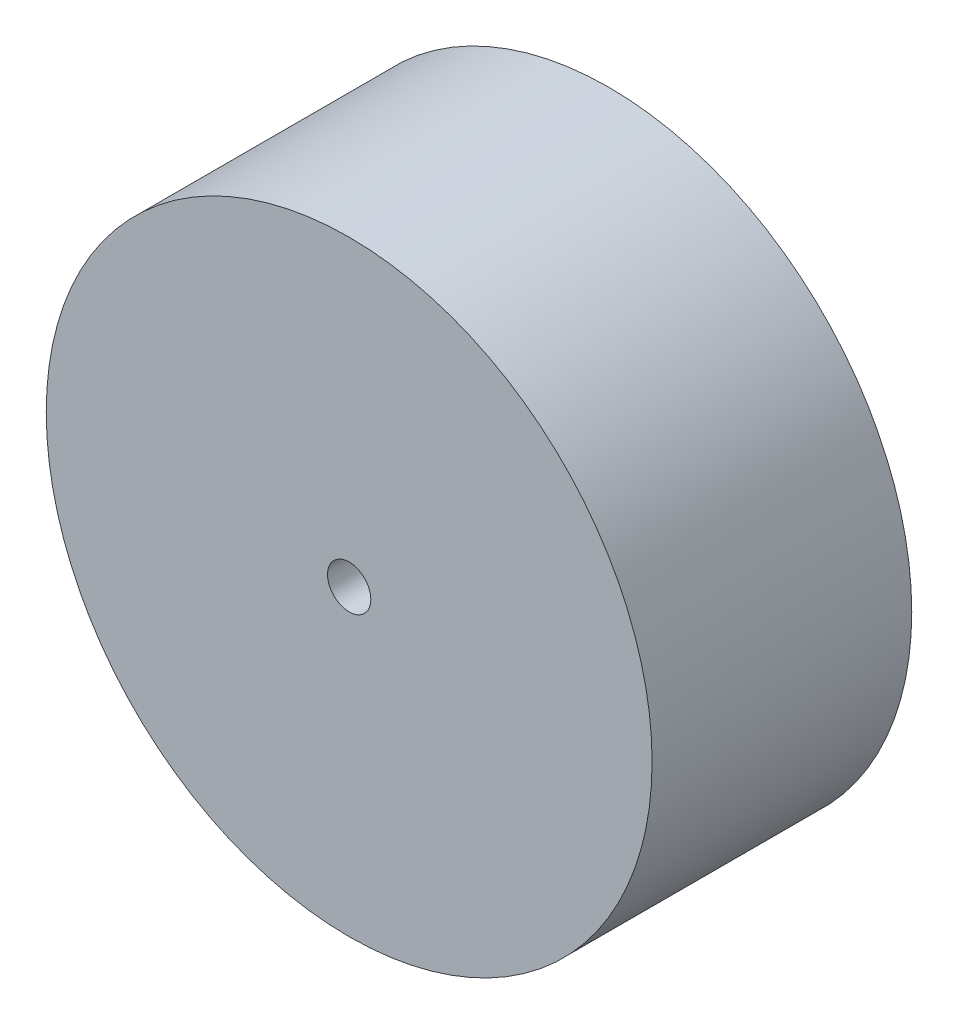
SolidWorks part; units mm, degrees
ref_plane "Front Plane" through (0, 0, 0) normal (0, 0, 1) x (1, 0, 0)
ref_plane "Top Plane" through (0, 0, 0) normal (0, 1, 0) x (1, 0, 0)
ref_plane "Right Plane" through (0, 0, 0) normal (1, 0, 0) x (0, 0, -1)
sketch "Sketch1" plane through (0, 0, 0) normal (0, 0, 1) x (1, 0, 0)
  circle A0 centre (0, 0) radius 35.56
  dimension "D1" = 71.12
extrude "Boss-Extrude1" add sketch "Sketch1" along normal blind 30.48 contours A0
sketch "Sketch2" plane through (0, 0, 30.48) normal (0, 0, 1) x (1, 0, 0)
  circle A0 centre (0, 0) radius 2.54
  circle A1 centre (0, 0) radius 35.56 construction
  dimension "D1" = 5.08
extrude "Cut-Extrude1" cut sketch "Sketch2" against normal blind 30.48
